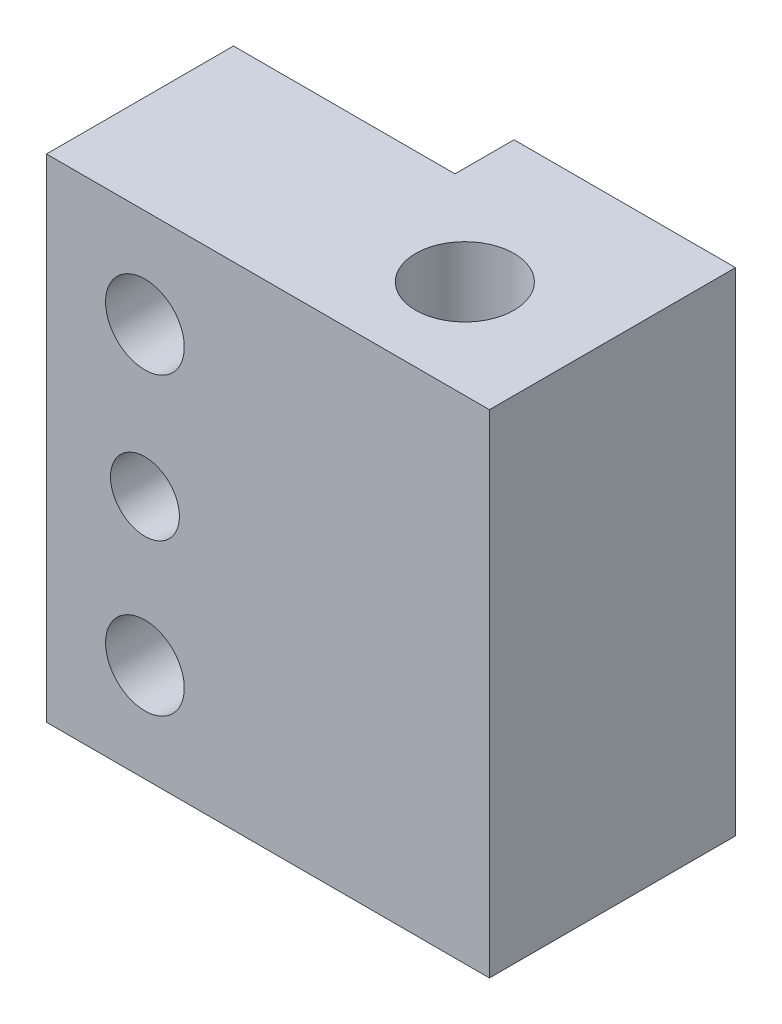
SolidWorks part; units mm, degrees
ref_plane "Front Plane" through (0, 0, 0) normal (0, 0, 1) x (1, 0, 0)
ref_plane "Top Plane" through (0, 0, 0) normal (0, 1, 0) x (1, 0, 0)
ref_plane "Right Plane" through (0, 0, 0) normal (1, 0, 0) x (0, 0, -1)
sketch "Sketch1" plane through (0, 0, 0) normal (0, 1, 0) x (1, 0, 0)
  line L0 (20, 3.8) -> (0, 3.8) construction
  line L1 (0, 0) -> (20, 0)
  line L2 (0, 0) -> (0, 5) construction
  line L3 (0, 5) -> (20, 5) construction
  line L4 (20, 0) -> (20, 5) construction
  line L5 (20, 0) -> (20, 5)
  line L6 (20, 5) -> (15.5, 5)
  line L7 (15.5, 5) -> (15.5, 3.8)
  line L8 (0, 3.8) -> (0, 0)
  line L10 (0, 3.8) -> (15.5, 3.8)
  circle A0 centre (2.5, 2) radius 1
  circle A1 centre (17.5, 2) radius 1
  dimension "D3" = 1.2
  dimension "D1" = 5
  dimension "D2" = 20
  dimension "D4" = 4.5
extrude "Boss-Extrude1" add sketch "Sketch1" along normal blind 10
sketch "Sketch5" plane through (0, 0, -3.8) normal (0, 0, -1) x (-1, 0, 0)
  line L0 (-10.1846, 10) -> (-10.1846, 0) construction
  line L1 (-15.5, 10) -> (0, 10) construction
  line L2 (-15.5, 0) -> (0, 0) construction
  line L3 (-9.1846, 10) -> (-9.1846, 0) construction
  line L4 (-3.5353, 10) -> (-3.5353, 0) construction
  line L5 (-2.1865, 10) -> (-2.1865, 0) construction
  circle A0 centre (-13, 4.9718) radius 0.7
  circle A1 centre (-13, 8) radius 0.8
  circle A2 centre (-6.5, 4) radius 2
  circle A3 centre (-13, 2) radius 0.8
  dimension "D1" = 1
  dimension "D2" = 2
extrude "Cut-Extrude3" cut sketch "Sketch5" against normal through all
sketch "Sketch7" plane through (0, 0, -3.8) normal (0, 0, -1) x (-1, 0, 0)
  line L1 (-11, 13.726) -> (0, 13.726)
  line L2 (-11, 13.726) -> (-11, -2.2081)
  line L3 (-11, -2.2081) -> (0, -2.2081)
  line L4 (0, 13.726) -> (0, -2.2081)
extrude "Cut-Extrude4" cut sketch "Sketch7" against normal through all
